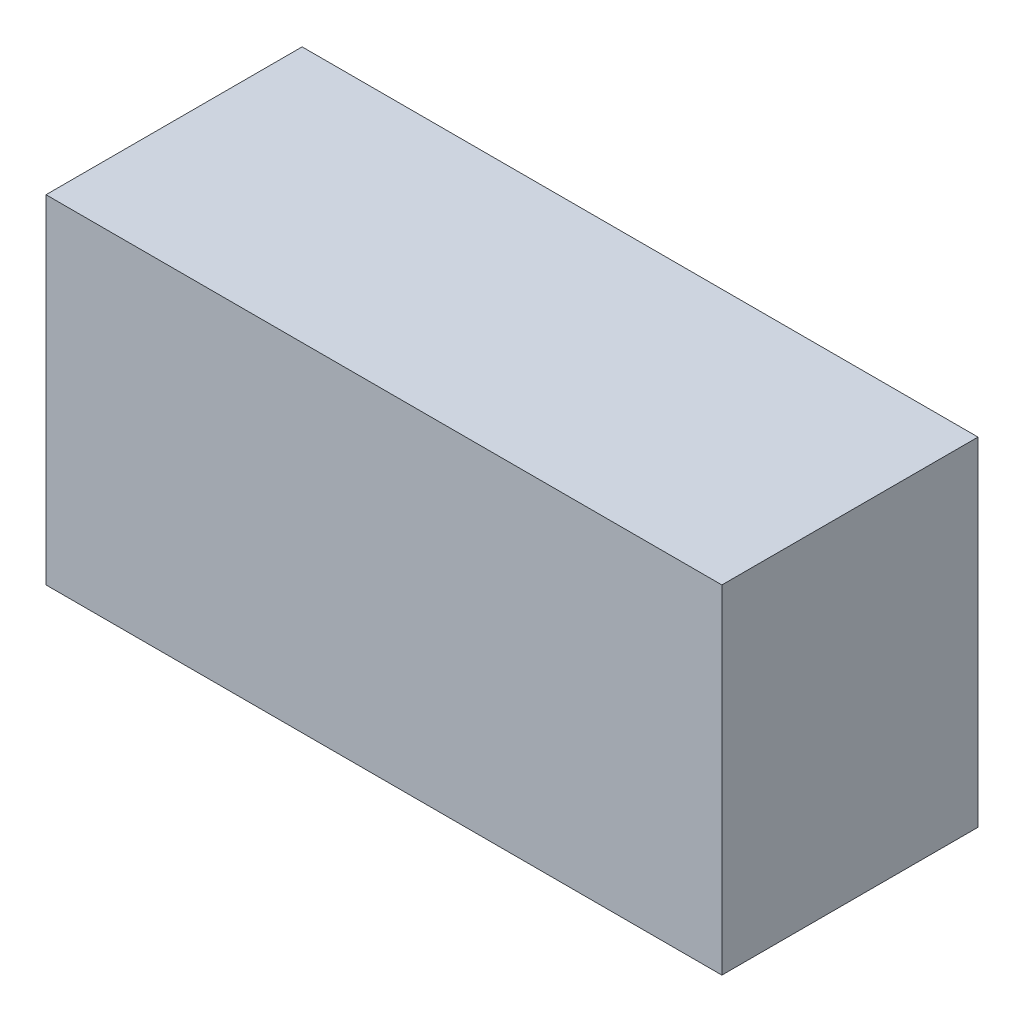
SolidWorks part; units mm, degrees
ref_plane "Front Plane" through (0, 0, 0) normal (0, 0, 1) x (1, 0, 0)
ref_plane "Top Plane" through (0, 0, 0) normal (0, 1, 0) x (1, 0, 0)
ref_plane "Right Plane" through (0, 0, 0) normal (1, 0, 0) x (0, 0, -1)
sketch "Sketch1" plane through (0, 0, 0) normal (0, 0, 1) x (1, 0, 0)
  line L1 (-50.8, -25.4) -> (50.8, -25.4)
  line L2 (-50.8, -25.4) -> (-50.8, 25.4)
  line L3 (-50.8, 25.4) -> (50.8, 25.4)
  line L4 (50.8, -25.4) -> (50.8, 25.4)
  line L5 (-50.8, -25.4) -> (50.8, 25.4) construction
  line L6 (-50.8, 25.4) -> (50.8, -25.4) construction
  point P0 (0, 0)
  dimension "D1" = 50.8
  dimension "D2" = 101.6
extrude "Boss-Extrude1" add sketch "Sketch1" along normal blind 38.5
